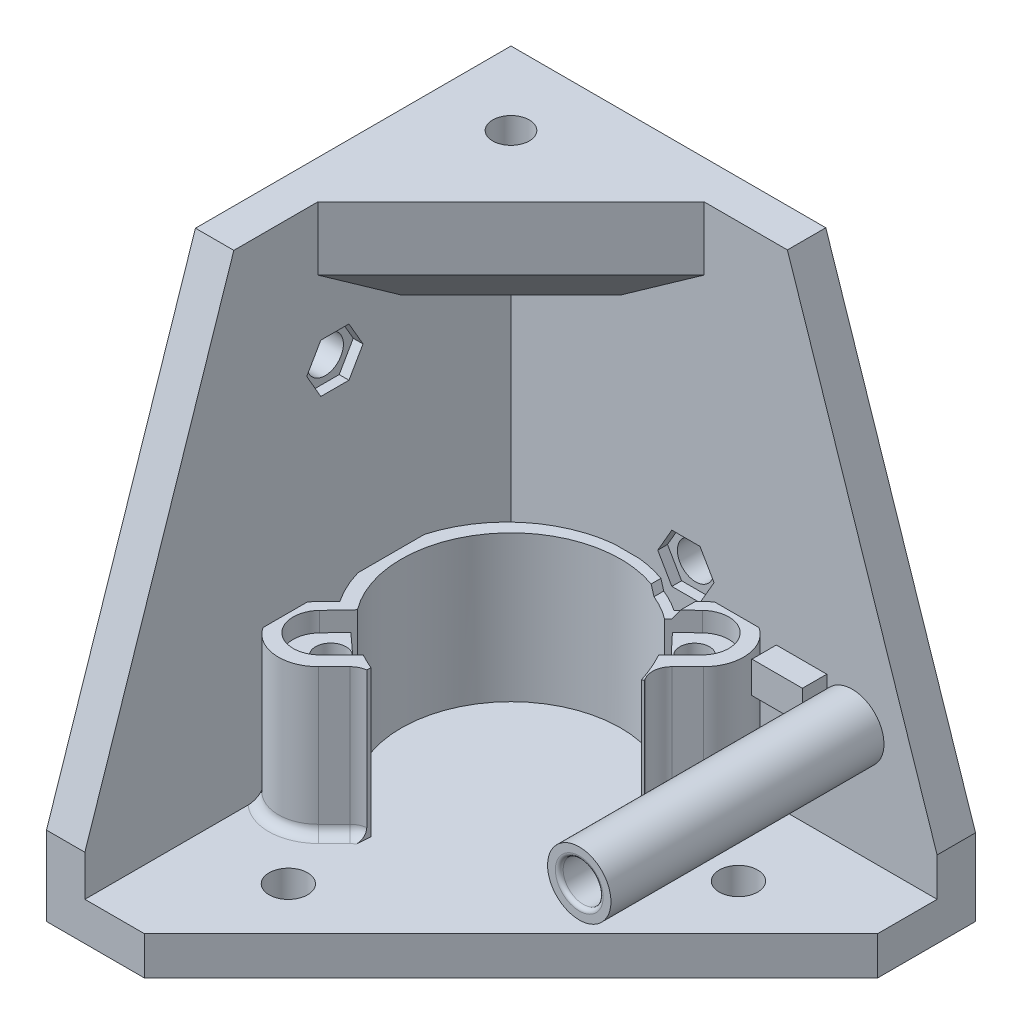
SolidWorks part; units mm, degrees
ref_plane "Front" through (0, 0, 0) normal (0, 0, 1) x (1, 0, 0)
ref_plane "Top" through (0, 0, 0) normal (0, 1, 0) x (1, 0, 0)
ref_plane "Right" through (0, 0, 0) normal (1, 0, 0) x (0, 0, -1)
sketch "Sketch1" plane through (0, 0, 0) normal (0, 1, 0) x (1, 0, 0)
  line L0 (0, 0) -> (0, 60.5)
  line L1 (0, -55) -> (0, 55) construction
  line L2 (0, 60.5) -> (60.5, 60.5)
  line L3 (60.5, 60.5) -> (60.5, 47.75)
  line L4 (60.5, 47.75) -> (12.75, 0)
  line L5 (-55, 0) -> (55, 0) construction
  line L6 (12.75, 0) -> (0, 0)
  dimension "D1" = 60.5
  dimension "D2" = 12.75
extrude "Boss-Extrude1" add sketch "Sketch1" along normal blind 5
sketch "Sketch4" plane through (0, 0, 0) normal (-1, 0, 0) x (0, 0, 1)
  line L0 (-60.5, 5) -> (-60.5, 68.5)
  line L1 (-60.5, 68.5) -> (-19.4, 68.5)
  line L2 (-19.4, 68.5) -> (0, 10.3086)
  line L3 (0, 10.3086) -> (0, 5)
  line L4 (0, -2.75) -> (0, 2.75) construction
  line L5 (-60.5, 5) -> (0, 5) construction
  line L6 (-60.5, 5) -> (0, 5)
  dimension "D1" = 63.5
  dimension "D2" = 41.1
  dimension "D3" = 61.34
extrude "Boss-Extrude2" add sketch "Sketch4" against normal blind 5
sketch "Sketch5" plane through (0, 0, -60.5) normal (0, 0, -1) x (-1, 0, 0)
  line L0 (0, 68.5) -> (-41, 68.5)
  line L1 (-41, 68.5) -> (-60.5, 10.0047)
  line L2 (-60.5, 10.0047) -> (-60.5, 5)
  line L6 (-60.5, 0) -> (0, 0)
  line L7 (0, 0) -> (0, 68.5)
  line L8 (0, 68.5) -> (-5, 68.5)
  line L9 (-5, 68.5) -> (-5, 5)
  line L10 (-5, 5) -> (-60.5, 5)
  line L11 (-60.5, 5) -> (-60.5, 0)
  line L12 (-60.5, 0) -> (0, 0)
  line L13 (0, 0) -> (0, 68.5)
  line L14 (0, 68.5) -> (-5, 68.5)
  line L15 (-5, 68.5) -> (-5, 5)
  line L16 (-5, 5) -> (-60.5, 5)
  line L17 (-60.5, 5) -> (-60.5, 0)
  line M13 (-5, 68.5) -> (-5, 5)
  line M14 (-5, 5) -> (-60.5, 5)
  dimension "D2" = 41
  dimension "D3" = 61.66
  dimension "D1" = 0
extrude "Boss-Extrude3" add sketch "Sketch5" against normal blind 5 contours L1 L2 L0 M14 M13
sketch "Sketch6" plane through (0, 5, 0) normal (0, 1, 0) x (1, 0, 0)
  line L0 (60.5, 60.5) -> (0, 60.5) construction
  line L4 (0, 19.4) -> (0, 0)
  line L5 (60.5, 55.5) -> (5, 55.5)
  line L6 (5, 55.5) -> (5, 0)
  line L7 (5, 0) -> (12.75, 0)
  line L8 (12.75, 0) -> (60.5, 47.75)
  line L9 (60.5, 47.75) -> (60.5, 55.5)
  line L10 (60.5, 55.5) -> (5, 55.5)
  line L11 (5, 55.5) -> (5, 0)
  line L12 (5, 0) -> (12.75, 0)
  line L13 (12.75, 0) -> (60.5, 47.75)
  line L14 (60.5, 47.75) -> (60.5, 55.5)
  line L15 (0, 0) -> (5, 0)
  line L16 (5, 0) -> (5, 19.4)
  line L17 (5, 19.4) -> (0, 19.4)
  line L18 (0, 19.4) -> (0, 0)
  line L19 (0, 0) -> (5, 0)
  line L20 (5, 0) -> (5, 19.4)
  line L21 (5, 19.4) -> (0, 19.4)
  line L24 (0, 60.5) -> (0, 19.4)
  line L25 (0, 19.4) -> (5, 19.4)
  line L26 (5, 19.4) -> (5, 55.5)
  line L27 (5, 55.5) -> (41, 55.5)
  line L28 (41, 55.5) -> (41, 60.5)
  line L29 (41, 60.5) -> (0, 60.5)
  line L30 (0, 60.5) -> (0, 19.4)
  line L31 (0, 19.4) -> (5, 19.4)
  line L32 (5, 19.4) -> (5, 55.5)
  line L33 (5, 55.5) -> (41, 55.5)
  line L34 (41, 55.5) -> (41, 60.5)
  line L35 (41, 60.5) -> (0, 60.5)
  circle A0 centre (16.5, 15) radius 2.5
  circle A1 centre (45.5, 44.625) radius 2.5
  dimension "D1" = 5
  dimension "D2" = 5
  dimension "D3" = 0
  dimension "D4" = 15
  dimension "D6" = 16.5
  dimension "D7" = 15
  dimension "D9" = 15.875
  dimension "D5" = 0
  dimension "D8" = 0
extrude "Cut-Extrude1" cut sketch "Sketch6" against normal through all contours A0 | A1
sketch "Sketch9" plane through (0, 0, -55.5) normal (0, 0, 1) x (1, 0, 0)
  line L1 (5, 68.5) -> (5, 5) construction
  line L5 (0, 0) -> (60.5, 0)
  line L6 (0, 68.5) -> (0, 0)
  line L7 (41, 68.5) -> (0, 68.5)
  line L8 (60.5, 10.0047) -> (41, 68.5)
  line L9 (60.5, 0) -> (60.5, 10.0047)
  line L10 (0, 0) -> (60.5, 0)
  line L11 (0, 68.5) -> (0, 0)
  line L12 (41, 68.5) -> (0, 68.5)
  line L13 (60.5, 10.0047) -> (41, 68.5)
  line L14 (60.5, 0) -> (60.5, 10.0047)
  line L15 (49.45, 19.0462) -> (49.45, 11.3161) construction
  circle A0 centre (49.45, 19.0462) radius 4.1275
  circle A1 centre (49.45, 19.0462) radius 2.6035
  dimension "D2" = 5.207
  dimension "D3" = 1.524
  dimension "D4" = 49.4538
  dimension "D5" = 44.45
  dimension "D1" = 0
extrude "Boss-Extrude5" add sketch "Sketch9" along normal blind 35.56
fillet "Fillet1" radius 0.508 1 edges at (52.0535, 19.0462, -19.94)
sketch "Sketch14" plane through (0, 5, 0) normal (0, 1, 0) x (1, 0, 0)
  line L0 (13.4627, 27.5396) -> (14.7681, 26.7924)
  line L1 (12.75, 0) -> (60.5, 47.75) construction
  line L2 (36.625, 23.875) -> (5, 55.5) construction
  line L3 (5, 55.5) -> (60.5, 55.5) construction
  line L4 (32.9604, 47.0373) -> (33.7076, 45.7319)
  line L5 (14.8281, 26.8523) -> (11.8274, 23.8516)
  line L6 (6.723, 28.8027) -> (9.1327, 31.3641)
  line L7 (33.6477, 45.6719) -> (36.6484, 48.6726)
  line L8 (31.6973, 53.777) -> (29.1359, 51.3673)
  line L9 (15.0744, 24.4582) -> (13.006, 22.3898)
  line L10 (5.6561, 29.7396) -> (7.0609, 31.1444)
  line L11 (36.0418, 45.4256) -> (38.1102, 47.494)
  line L12 (30.7604, 54.8439) -> (28.83, 52.9135)
  line L13 (18.1324, 24.8665) -> (30.5234, 17.7734)
  line L14 (35.6335, 42.3676) -> (42.7266, 29.9766)
  line L15 (31.7409, 18.9909) -> (18.852, 25.7543)
  line L16 (41.5091, 28.7591) -> (34.7457, 41.648)
  line L17 (16.5689, 25.6946) -> (16.5343, 25.1798)
  line L18 (34.7457, 41.648) -> (35.7996, 42.0774)
  circle A0 centre (20.5607, 39.9393) radius 14.2875
  arc A1 (11.8274, 23.8516) -> (6.723, 28.8027) centre (9.3129, 26.3661) cw
  arc A2 (36.6484, 48.6726) -> (31.6973, 53.777) centre (34.1339, 51.1871) ccw
  arc A3 (13.006, 22.3898) -> (5.6561, 29.7396) centre (9.3311, 26.0647) cw
  arc A4 (38.1102, 47.494) -> (30.7604, 54.8439) centre (34.4353, 51.1689) ccw
  arc A5 (7.0609, 31.1444) -> (28.83, 52.9135) centre (20.0709, 39.9035) cw
  arc A6 (36.0418, 45.4256) -> (35.6335, 42.3676) centre (37.8378, 43.6295) ccw
  arc A7 (15.0744, 24.4582) -> (18.1324, 24.8665) centre (16.8705, 22.6622) cw
  arc A9 (33.8602, 45.8844) -> (36.3595, 38.5726) centre (13.6025, 34.877) cw
  arc A10 (14.6156, 26.6398) -> (21.9274, 24.1405) centre (25.623, 46.8975) ccw
  point P40 (34.6689, 44.0527)
  point P43 (16.4473, 25.8311)
  line M13 (60.5, 55.5) -> (5, 55.5)
  line M14 (5, 55.5) -> (5, 0)
  line M16 (12.75, 0) -> (60.5, 47.75)
  dimension "D1" = 28.575
  dimension "D2" = 3.556
  dimension "D3" = 2.54
extrude "Boss-Extrude6" add sketch "Sketch14" along normal blind 19.05 contours L2 A0 L5 A1 L6 A5 L10 A3 L9 A7 L13 M16 M14 | L2 L14 A6 L11 A4 L12 A5 A0 L8 A2 L7 M16 M13
sketch "Sketch15" plane through (0, 68.5, 0) normal (0, 1, 0) x (1, 0, 0)
  line L0 (5, 30.3375) -> (30.1625, 55.5)
  line L1 (0, -33.275) -> (0, 33.275) construction
  line L2 (41, 60.5) -> (0, 60.5) construction
  line L6 (0, 60.5) -> (0, 19.4)
  line L7 (0, 19.4) -> (5, 19.4)
  line L8 (5, 19.4) -> (5, 55.5)
  line L9 (5, 55.5) -> (41, 55.5)
  line L10 (41, 55.5) -> (41, 60.5)
  line L11 (41, 60.5) -> (0, 60.5)
  line L13 (0, 19.4) -> (5, 19.4)
  line L14 (5, 30.3375) -> (5, 55.5)
  line L15 (5, 55.5) -> (30.1625, 55.5)
  line L16 (41, 55.5) -> (41, 60.5)
  circle A0 centre (9.525, 50.975) radius 2.3812
  line M11 (5, 19.4) -> (5, 55.5)
  line M12 (5, 55.5) -> (41, 55.5)
  dimension "D3" = 4.7625
  dimension "D4" = 9.525
  dimension "D5" = 9.525
  dimension "D2" = 45
  dimension "D1" = 0
extrude "Boss-Extrude7" add sketch "Sketch15" against normal blind 15.875 contours L0 A0 M11 M12
chamfer "Chamfer2" distance 7.62 angle 45 1 edges at (17.5813, 52.625, -42.9187)
fillet "Fillet2" radius 1.27 7 edges at (39.6065, 5, -51.6871) (37.076, 5, -46.4598) (35.3202, 5, -43.9657) (8.8129, 5, -20.8935) (14.0402, 5, -23.424) (15.745, 5, -24.9392) (35.7165, 5, -42.2225)
sketch "Sketch16" plane through (0, 0, -55.5) normal (0, 0, 1) x (1, 0, 0)
  line L1 (46.1305, 23.2107) -> (38.2864, 23.2107)
  line L2 (46.1305, 23.2107) -> (46.1305, 19.0978)
  line L3 (46.1305, 19.0978) -> (38.2864, 19.0978)
  line L4 (38.2864, 23.2107) -> (38.2864, 19.0978)
extrude "Boss-Extrude8" add sketch "Sketch16" along normal blind 3.175
chamfer "Chamfer3" distance 1.27 angle 45 1 edges at (38.2864, 23.2107, -55.0794)
sketch "Sketch17" plane through (0, 5, 0) normal (0, 1, 0) x (1, 0, 0)
  line L0 (8.716, 30.9212) -> (14.047, 26.0712)
  line L1 (36.625, 23.875) -> (5, 55.5) construction
  line L2 (12.75, 0) -> (60.5, 47.75) construction
  line L3 (5, 55.5) -> (18.418, 55.5) construction
  line L4 (5, 55.5) -> (5, 44.2452) construction
  line L5 (29.6632, 51.8634) -> (34.5959, 46.6202)
  line L22 (37.3079, 55.5) -> (31.5627, 55.5)
  line L23 (30.7604, 54.8439) -> (28.83, 52.9135)
  line L24 (21.7238, 55.5) -> (18.418, 55.5)
  line L25 (5, 44.2452) -> (5, 35.5618)
  line L26 (7.0609, 31.1444) -> (5.6561, 29.7396)
  line L27 (5, 28.9373) -> (5, 23.1921)
  line L28 (13.006, 22.3898) -> (15.0744, 24.4582)
  line L29 (16.5343, 25.1798) -> (16.5689, 25.6946)
  line L30 (16.5343, 25.1798) -> (16.5689, 25.6946)
  line L31 (35.539, 41.9712) -> (35.7996, 42.0774)
  line L32 (35.539, 41.9712) -> (35.7996, 42.0774)
  line L33 (14.6156, 26.6398) -> (11.8274, 23.8516)
  line L34 (6.723, 28.8027) -> (9.1327, 31.3641)
  line L35 (29.1359, 51.3673) -> (31.6973, 53.777)
  line L36 (36.6484, 48.6726) -> (33.8602, 45.8844)
  line L40 (35.7996, 42.0774) -> (35.6335, 42.3676)
  line L41 (36.0418, 45.4256) -> (38.1102, 47.494)
  line L43 (37.3079, 55.5) -> (31.5627, 55.5)
  line L44 (30.7604, 54.8439) -> (28.83, 52.9135)
  line L45 (21.7238, 55.5) -> (18.418, 55.5)
  line L46 (5, 44.2452) -> (5, 35.5618)
  line L47 (7.0609, 31.1444) -> (5.6561, 29.7396)
  line L48 (5, 28.9373) -> (5, 23.1921)
  line L49 (13.006, 22.3898) -> (15.0744, 24.4582)
  line L54 (14.6156, 26.6398) -> (11.8274, 23.8516)
  line L55 (6.723, 28.8027) -> (9.1327, 31.3641)
  line L56 (29.1359, 51.3673) -> (31.6973, 53.777)
  line L57 (36.6484, 48.6726) -> (33.8602, 45.8844)
  line L61 (35.7996, 42.0774) -> (35.6335, 42.3676)
  line L62 (36.0418, 45.4256) -> (38.1102, 47.494)
  circle A1 centre (33.6908, 50.7324) radius 2.1828
  circle A2 centre (10.0204, 27.0078) radius 1.9844
  circle A3 centre (33.6908, 50.7324) radius 1.9288
  arc A15 (38.1102, 47.494) -> (37.3079, 55.5) centre (34.4353, 51.1689) ccw
  arc A17 (31.5627, 55.5) -> (30.7604, 54.8439) centre (34.4353, 51.1689) ccw
  arc A18 (28.83, 52.9135) -> (21.7238, 55.5) centre (20.0709, 39.9035) ccw
  arc A19 (18.418, 55.5) -> (5, 44.2452) centre (20.0709, 39.9035) ccw
  arc A20 (5, 35.5618) -> (7.0609, 31.1444) centre (20.0709, 39.9035) ccw
  arc A21 (5.6561, 29.7396) -> (5, 28.9373) centre (9.3311, 26.0647) ccw
  arc A22 (5, 23.1921) -> (13.006, 22.3898) centre (9.3311, 26.0647) ccw
  arc A23 (16.5343, 25.1798) -> (15.0744, 24.4582) centre (16.8705, 22.6622) ccw
  arc A24 (14.6156, 26.6398) -> (16.5689, 25.6946) centre (25.623, 46.8975) ccw
  arc A25 (6.723, 28.8027) -> (11.8274, 23.8516) centre (9.3129, 26.3661) ccw
  arc A26 (29.1359, 51.3673) -> (9.1327, 31.3641) centre (20.5607, 39.9393) ccw
  arc A27 (36.6484, 48.6726) -> (31.6973, 53.777) centre (34.1339, 51.1871) ccw
  arc A28 (35.539, 41.9712) -> (33.8602, 45.8844) centre (13.6025, 34.877) ccw
  arc A29 (36.0418, 45.4256) -> (35.6335, 42.3676) centre (37.8378, 43.6295) ccw
  arc A30 (38.1102, 47.494) -> (37.3079, 55.5) centre (34.4353, 51.1689) ccw
  arc A32 (31.5627, 55.5) -> (30.7604, 54.8439) centre (34.4353, 51.1689) ccw
  arc A33 (28.83, 52.9135) -> (21.7238, 55.5) centre (20.0709, 39.9035) ccw
  arc A34 (18.418, 55.5) -> (5, 44.2452) centre (20.0709, 39.9035) ccw
  arc A35 (5, 35.5618) -> (7.0609, 31.1444) centre (20.0709, 39.9035) ccw
  arc A36 (5.6561, 29.7396) -> (5, 28.9373) centre (9.3311, 26.0647) ccw
  arc A37 (5, 23.1921) -> (13.006, 22.3898) centre (9.3311, 26.0647) ccw
  arc A38 (16.5343, 25.1798) -> (15.0744, 24.4582) centre (16.8705, 22.6622) ccw
  arc A39 (14.6156, 26.6398) -> (16.5689, 25.6946) centre (25.623, 46.8975) ccw
  arc A40 (6.723, 28.8027) -> (11.8274, 23.8516) centre (9.3129, 26.3661) ccw
  arc A41 (29.1359, 51.3673) -> (9.1327, 31.3641) centre (20.5607, 39.9393) ccw
  arc A42 (36.6484, 48.6726) -> (31.6973, 53.777) centre (34.1339, 51.1871) ccw
  arc A43 (35.539, 41.9712) -> (33.8602, 45.8844) centre (13.6025, 34.877) ccw
  arc A44 (36.0418, 45.4256) -> (35.6335, 42.3676) centre (37.8378, 43.6295) ccw
  dimension "D2" = 3.9688
  dimension "D3" = 0.254
  dimension "D1" = 0
extrude "Boss-Extrude9" add sketch "Sketch17" along normal offset from surface (16.51 mm away) 2.54
sketch "Sketch18" plane through (0, 0, 0) normal (-1, 0, 0) x (0, 0, 1)
  line L0 (-60.5, 68.5) -> (-60.5, 0) construction
  line L1 (33.275, 0) -> (-33.275, 0) construction
  circle A0 centre (-32.56, 49.53) radius 2.3813
  dimension "D1" = 27.94
  dimension "D2" = 49.53
  dimension "D3" = 4.7625
extrude "Cut-Extrude2" cut sketch "Sketch18" against normal up to next
sketch "Sketch19" plane through (0, 0, -60.5) normal (0, 0, -1) x (-1, 0, 0)
  line L0 (0, 33.275) -> (0, -33.275) construction
  line L1 (33.275, 0) -> (-33.275, 0) construction
  circle A0 centre (-27.7812, 26.1937) radius 2.3813
  dimension "D1" = 27.7812
  dimension "D2" = 26.1937
  dimension "D3" = 4.7625
extrude "Cut-Extrude3" cut sketch "Sketch19" against normal up to next
sketch "Sketch20" plane through (0, 0, -55.5) normal (0, 0, 1) x (1, 0, 0)
  line L1 (31.4474, 26.1937) -> (29.6143, 29.3687)
  line L2 (29.6143, 29.3687) -> (25.9482, 29.3687)
  line L3 (25.9482, 29.3687) -> (24.1151, 26.1937)
  line L4 (24.1151, 26.1937) -> (25.9482, 23.0187)
  line L5 (25.9482, 23.0187) -> (29.6143, 23.0187)
  line L6 (29.6143, 23.0187) -> (31.4474, 26.1937)
  circle A0 centre (27.7812, 26.1937) radius 2.3813 construction
  circle A1 centre (27.7812, 26.1937) radius 2.3813
  circle A2 centre (27.7812, 26.1937) radius 3.175 construction
  dimension "D1" = 6.35
extrude "Cut-Extrude4" cut sketch "Sketch20" against normal blind 1.27 and the other way up to vertex (4.1327 mm away) contours L1 L2 L3 L4 L5 L6 other way up to point (29.1359, 5, -51.3673)
sketch "Sketch21" plane through (5, 0, 0) normal (1, 0, 0) x (0, 0, -1)
  line L1 (34.3931, 52.705) -> (30.7269, 52.705)
  line L2 (30.7269, 52.705) -> (28.8938, 49.53)
  line L3 (28.8938, 49.53) -> (30.7269, 46.355)
  line L4 (30.7269, 46.355) -> (34.3931, 46.355)
  line L5 (34.3931, 46.355) -> (36.2262, 49.53)
  line L6 (36.2262, 49.53) -> (34.3931, 52.705)
  circle A0 centre (32.56, 49.53) radius 2.3813 construction
  circle A1 centre (32.56, 49.53) radius 2.3812
  circle A2 centre (32.56, 49.53) radius 3.175 construction
  dimension "D1" = 6.35
extrude "Cut-Extrude5" cut sketch "Sketch21" against normal blind 1.27 contours L1 L2 L3 L4 L5 L6
